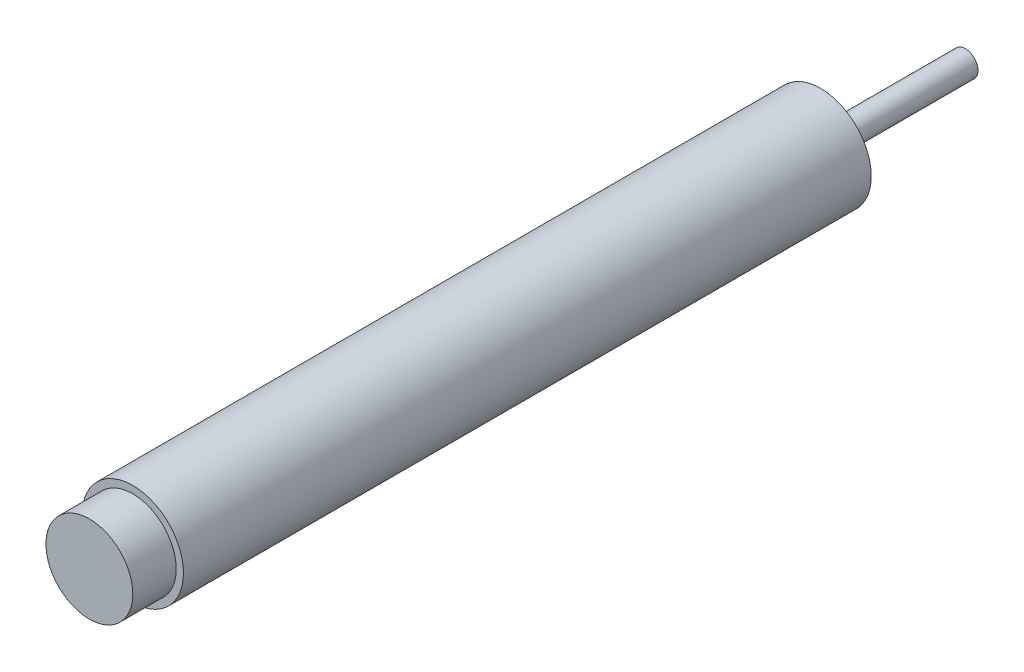
SolidWorks part; units mm, degrees
ref_plane "前视基准面" through (0, 0, 0) normal (0, 0, 1) x (1, 0, 0)
ref_plane "上视基准面" through (0, 0, 0) normal (0, 1, 0) x (1, 0, 0)
ref_plane "右视基准面" through (0, 0, 0) normal (1, 0, 0) x (0, 0, -1)
sketch "草图1" plane through (0, 0, 0) normal (0, 0, 1) x (1, 0, 0)
  circle A0 centre (0, 0) radius 7
  dimension "D1" = 14
extrude "拉伸1" add sketch "草图1" along normal blind 95
sketch "草图2" plane through (0, 0, 0) normal (0, 0, -1) x (-1, 0, 0)
  circle A0 centre (0, 0) radius 1.75
  dimension "D1" = 3.5
extrude "拉伸2" add sketch "草图2" along normal blind 20
sketch "草图3" plane through (0, 0, 95) normal (0, 0, 1) x (1, 0, 0)
  circle A0 centre (0, 0) radius 6
  dimension "D1" = 12
extrude "拉伸3" add sketch "草图3" along normal blind 6
